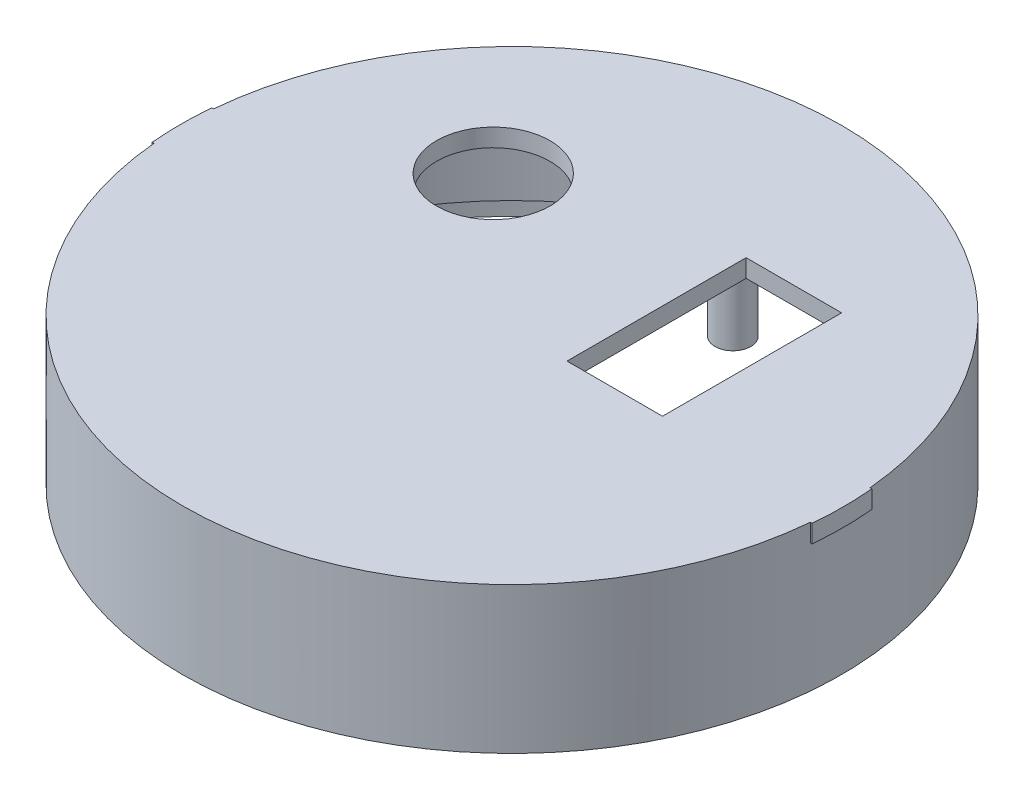
SolidWorks part; units mm, degrees
ref_plane "Front Plane" through (0, 0, 0) normal (0, 0, 1) x (1, 0, 0)
ref_plane "Top Plane" through (0, 0, 0) normal (0, 1, 0) x (1, 0, 0)
ref_plane "Right Plane" through (0, 0, 0) normal (1, 0, 0) x (0, 0, -1)
sketch "Sketch1" plane through (0, 0, 0) normal (0, 1, 0) x (1, 0, 0)
  circle A1 centre (0, 0) radius 55.2
  dimension "D2" = 110.4
extrude "Boss-Extrude1" add sketch "Sketch1" along normal blind 3
sketch "Sketch2" plane through (0, 3, 0) normal (0, 1, 0) x (1, 0, 0)
  circle A0 centre (0, 0) radius 55
  dimension "D1" = 110
extrude "Cut-Extrude1" cut sketch "Sketch2" against normal through all
sketch "Sketch4" plane through (0, 3, 0) normal (0, 1, 0) x (1, 0, 0)
  line L0 (0, 0) -> (8.2385, 0) construction
  line L1 (8.2385, 0) -> (0, 0) construction
  line L2 (0, 0) -> (0, 11.6273) construction
  line L3 (-45.2, -5) -> (-45.2, 5)
  line L4 (-45.2, -5) -> (-53.768, -5)
  line L5 (-45.2, 5) -> (-53.768, 5)
  circle A1 centre (0, 0) radius 55.2
  circle A2 centre (0, 0) radius 55.2
  arc A3 (-53.768, -5) -> (-53.768, 5) centre (0, 0) ccw
  point P12 (-45.2, 0)
  dimension "D2" = 110.4
  dimension "D3" = 108
  dimension "D4" = 10
  dimension "D5" = 10
  dimension "D1" = 0
extrude "Boss-Extrude2" add sketch "Sketch4" along normal blind 18.5
sketch "Sketch8" plane through (0, 3, 0) normal (0, -1, 0) x (1, 0, 0)
  line L2 (-53.768, -5) -> (-45.2, -5) construction
  line L3 (-45.2, 5) -> (-54.7723, 5)
  line L4 (-45.2, 5) -> (-45.2, -5)
  line L5 (-45.2, -5) -> (-54.7723, -5)
  circle A2 centre (0, 0) radius 55 construction
  arc A3 (-54.7723, 5) -> (-54.7723, -5) centre (0, 0) ccw
extrude "Boss-Extrude4" add sketch "Sketch8" along normal blind 3
sketch "Sketch6" plane through (0, 21.5, 0) normal (0, 1, 0) x (1, 0, 0)
  line L1 (11.2131, 28) -> (27.2131, 28)
  line L2 (11.2131, 28) -> (11.2131, -2)
  line L3 (11.2131, -2) -> (27.2131, -2)
  line L4 (27.2131, 28) -> (27.2131, -2)
  line L5 (11.2131, 28) -> (27.2131, -2) construction
  line L6 (11.2131, -2) -> (27.2131, 28) construction
  line L7 (12.1174, 28) -> (26.3174, 28) construction
  line L9 (0, 0) -> (-136.4299, 0) construction
  line L15 (-55.2743, -5) -> (-54.9731, -5)
  line L17 (0, 0) -> (0, 23.5681) construction
  line L18 (-55.2743, 5) -> (-54.9731, 5)
  line L19 (55.2743, -5) -> (54.9731, -5)
  line L20 (55.2743, 5) -> (54.9731, 5)
  arc A0 (-54.9731, -5) -> (54.9731, -5) centre (0, 0) ccw
  circle A1 centre (-22.2011, 19.0599) radius 9.5
  arc A2 (-55.2743, 5) -> (-55.2743, -5) centre (0, 0) ccw
  arc A3 (55.2743, 5) -> (55.2743, -5) centre (0, 0) cw
  arc A4 (54.9731, 5) -> (-54.9731, 5) centre (0, 0) ccw
  point P5 (19.2131, 13)
  dimension "D1" = 19
  dimension "D2" = 30
  dimension "D3" = 16
  dimension "D6" = 110.4
  dimension "D9" = 111
  dimension "D4" = 19.2131
  dimension "D5" = 13
  dimension "D7" = 19.0599
  dimension "D8" = 22.2011
  dimension "D10" = 10
extrude "Boss-Extrude3" add sketch "Sketch6" along normal blind 3
sketch "Sketch15" plane through (0, 3, 0) normal (0, -1, 0) x (1, 0, 0)
  line L0 (0, 0) -> (0, 9.6411) construction
  line L1 (0, 0) -> (7.7973, 0) construction
  circle A1 centre (0, 42) radius 3
  circle A3 centre (0, -37) radius 3
  dimension "D2" = 37
  dimension "D4" = 6
  dimension "D1" = 6
  dimension "D3" = 42
extrude "Boss-Extrude9" add sketch "Sketch15" against normal up to next
hole_wizard "Ø3.0mm Dowel Hole2" positions "3DSketch4" profile "Sketch17" hole size "Ø3.0" standard "DIN"
sketch3d "3DSketch4"
  line L0 (0, 21.5, 42) -> (0, 3, 42) construction
  line L1 (0, 21.5, -37) -> (0, 3, -37) construction
  point P0 (0, 3, 42)
  point P4 (0, 3, -37)
sketch "Sketch17" plane through (0, 3, 42) normal (1, 0, 0) x (0, 0, -1)
  line L0 (0, 0) -> (0, 14.9013)
  line L1 (0, 14.9013) -> (1.5, 14)
  line L2 (1.5, 14) -> (1.5, 0)
  line L5 (1.5, 0) -> (0, 0)
  line L10 (0, 14.9013) -> (-1.5, 14) construction
  line L11 (0, -6.35) -> (0, 107.95) construction
  dimension "Hole Dia." = 3
  dimension "Hole Depth" = 14
  dimension "Drill Angle" = 118
